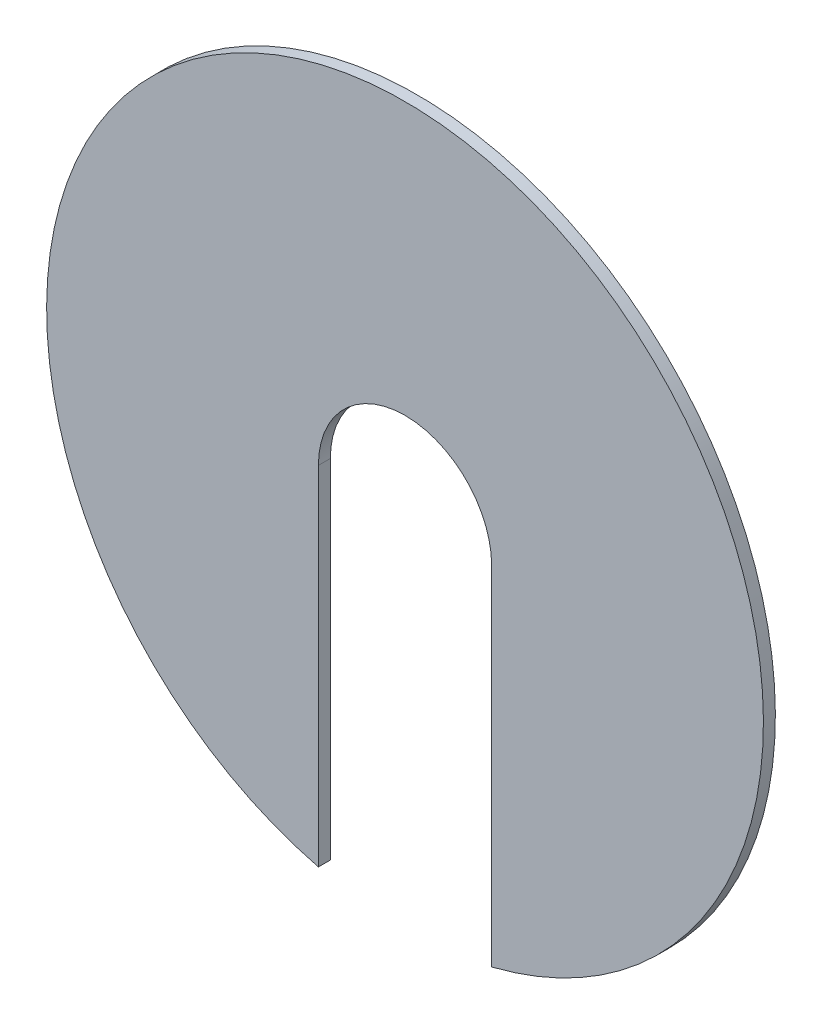
SolidWorks part; units mm, degrees
ref_plane "Front Plane" through (0, 0, 0) normal (0, 0, 1) x (1, 0, 0)
ref_plane "Top Plane" through (0, 0, 0) normal (0, 1, 0) x (1, 0, 0)
ref_plane "Right Plane" through (0, 0, 0) normal (1, 0, 0) x (0, 0, -1)
sketch "Sketch1" plane through (0, 0, 0) normal (0, 0, 1) x (1, 0, 0)
  line L0 (0, 12.8041) -> (0, -8.6127) construction
  line L1 (-13.1823, 0) -> (11.8393, 0) construction
  line L2 (-7.25, 0) -> (-7.25, -29.1108)
  line L3 (7.25, 0) -> (7.25, -29.1108)
  arc A0 (7.25, -29.1108) -> (-7.25, -29.1108) centre (0, 0) ccw
  arc A1 (7.25, 0) -> (-7.25, 0) centre (0, 0) ccw
  arc A2 (-7.25, 0) -> (0, -7.25) centre (0, 0) ccw construction
  arc A3 (0, -7.25) -> (7.25, 0) centre (0, 0) ccw construction
  arc A4 (-7.25, -29.1108) -> (7.25, -29.1108) centre (0, 0) ccw construction
  dimension "D1" = 60
  dimension "D2" = 14.5
extrude "Boss-Extrude1" add sketch "Sketch1" along normal mid plane 1
